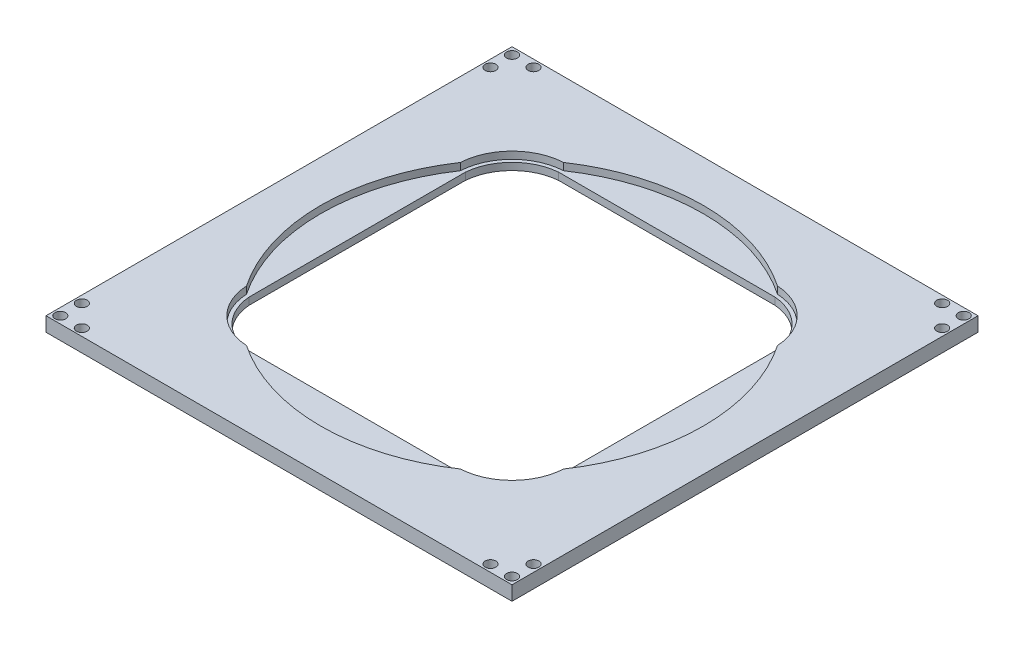
SolidWorks part; units mm, degrees
ref_plane "Front Plane" through (0, 0, 0) normal (0, 0, 1) x (1, 0, 0)
ref_plane "Top Plane" through (0, 0, 0) normal (0, 1, 0) x (1, 0, 0)
ref_plane "Right Plane" through (0, 0, 0) normal (1, 0, 0) x (0, 0, -1)
sketch "Sketch1" plane through (0, 0, 0) normal (0, 1, 0) x (1, 0, 0)
  line L1 (-65, 65) -> (65, 65)
  line L2 (-65, 65) -> (-65, -65)
  line L3 (-65, -65) -> (65, -65)
  line L4 (65, 65) -> (65, -65)
  line L5 (-65, 65) -> (65, -65) construction
  line L6 (-65, -65) -> (65, 65) construction
  point P0 (0, 0)
  dimension "D1" = 130
  dimension "D2" = 130
extrude "Boss-Extrude1" add sketch "Sketch1" along normal blind 4
sketch "Sketch4" plane through (0, 4, 0) normal (0, 1, 0) x (1, 0, 0)
  circle A1 centre (0, 0) radius 14 construction
  circle A2 centre (29, 0) radius 14 construction
  circle A3 centre (-29, 0) radius 14 construction
  circle A5 centre (0, -29) radius 14 construction
  circle A8 centre (0, 29) radius 14 construction
  arc A22 (-26.0405, 42.6836) -> (-42.6836, 26.0405) centre (-29, 29) ccw [skipped]
  arc A30 (42.6836, 26.0405) -> (26.0405, 42.6836) centre (29, 29) ccw [skipped]
  arc A32 (-29.5084, 43.2409) -> (-43.2409, 29.5084) centre (-29, 29) ccw
  arc A34 (-43.2409, -29.5084) -> (-29.5084, -43.2409) centre (-29, -29) ccw
  arc A36 (29.5084, -43.2409) -> (43.2409, -29.5084) centre (29, -29) ccw
  arc A38 (43.2409, 29.5084) -> (29.5084, 43.2409) centre (29, 29) ccw
  arc A39 (29.5084, 43.2409) -> (-29.5084, 43.2409) centre (0, 0) ccw
  arc A40 (-43.2409, 29.5084) -> (-43.2409, -29.5084) centre (0, 0) ccw
  arc A41 (-29.5084, -43.2409) -> (29.5084, -43.2409) centre (0, 0) ccw
  arc A42 (43.2409, -29.5084) -> (43.2409, 29.5084) centre (0, 0) ccw
  dimension "D1" = 104.7
  dimension "D2" = 28
  dimension "D3" = 29
  dimension "D4" = 29
  dimension "D7" = 2
sketch "Sketch5" plane through (0, 4, 0) normal (0, 1, 0) x (1, 0, 0)
  arc A0 (29.836, 44.2271) -> (-29.836, 44.2271) centre (0, 0) ccw
  arc A1 (-29.836, 44.2271) -> (-44.2271, 29.836) centre (-29, 29) ccw
  arc A2 (-44.2271, 29.836) -> (-44.2271, -29.836) centre (0, 0) ccw
  arc A3 (-44.2271, -29.836) -> (-29.836, -44.2271) centre (-29, -29) ccw
  arc A4 (-29.836, -44.2271) -> (29.836, -44.2271) centre (0, 0) ccw
  arc A5 (29.836, -44.2271) -> (44.2271, -29.836) centre (29, -29) ccw
  arc A6 (44.2271, -29.836) -> (44.2271, 29.836) centre (0, 0) ccw
  arc A7 (44.2271, 29.836) -> (29.836, 44.2271) centre (29, 29) ccw
extrude "Cut-Extrude1" cut sketch "Sketch5" against normal blind 4
sketch "Sketch6" plane through (0, 0, 0) normal (0, -1, 0) x (1, 0, 0)
  line L0 (-30.169, 43.1898) -> (30.169, 43.1898)
  line L1 (-30.169, 43.1898) -> (-30.169, 54.5427)
  line L2 (30.169, 43.1898) -> (30.169, 54.5427)
  line L3 (-30.169, 54.5427) -> (30.169, 54.5427)
extrude "Boss-Extrude2" add sketch "Sketch6" against normal blind 2
pattern_circular "CirPattern1" count 4 over 360 about axis through (0, 0, 0) along (0, 1, 0) of "Boss-Extrude2"
sketch "Sketch9" plane through (0, 0, 0) normal (0, -1, 0) x (1, 0, 0)
  line L0 (-30.169, 43.1898) -> (30.169, 43.1898) construction
  line L1 (-30.169, 44.2051) -> (-30.169, 43.1898)
  line L2 (-44.2051, 30.169) -> (-43.1898, 30.169)
  arc A0 (-43.1898, 30.169) -> (-30.169, 43.1898) centre (-29, 29) cw
  arc A1 (-30.169, 44.2051) -> (-44.2051, 30.169) centre (-29, 29) ccw construction
  arc A2 (-30.169, 44.2051) -> (-44.2051, 30.169) centre (-29, 29) ccw
extrude "Boss-Extrude3" add sketch "Sketch9" against normal blind 2
pattern_circular "CirPattern2" count 4 over 360 about axis through (0, 0, 0) along (0, 1, 0) of "Boss-Extrude3"
sketch "Sketch10" plane through (0, 4, 0) normal (0, 1, 0) x (1, 0, 0)
  line L0 (65, 65) -> (-65, 65) construction
  line L1 (-65, 65) -> (-65, -65) construction
  circle A0 centre (-63, 63) radius 1.5
  circle A1 centre (-57, 63) radius 1.5
  circle A2 centre (-63, 57) radius 1.5
  dimension "D2" = 3
  dimension "D4" = 3
  dimension "D7" = 3
  dimension "D1" = 2
  dimension "D3" = 2
  dimension "D5" = 6
  dimension "D8" = 6
extrude "Cut-Extrude2" cut sketch "Sketch10" against normal through all
pattern_circular "CirPattern3" count 4 over 360 about axis through (0, 0, 0) along (0, 1, 0) of "Cut-Extrude2"
